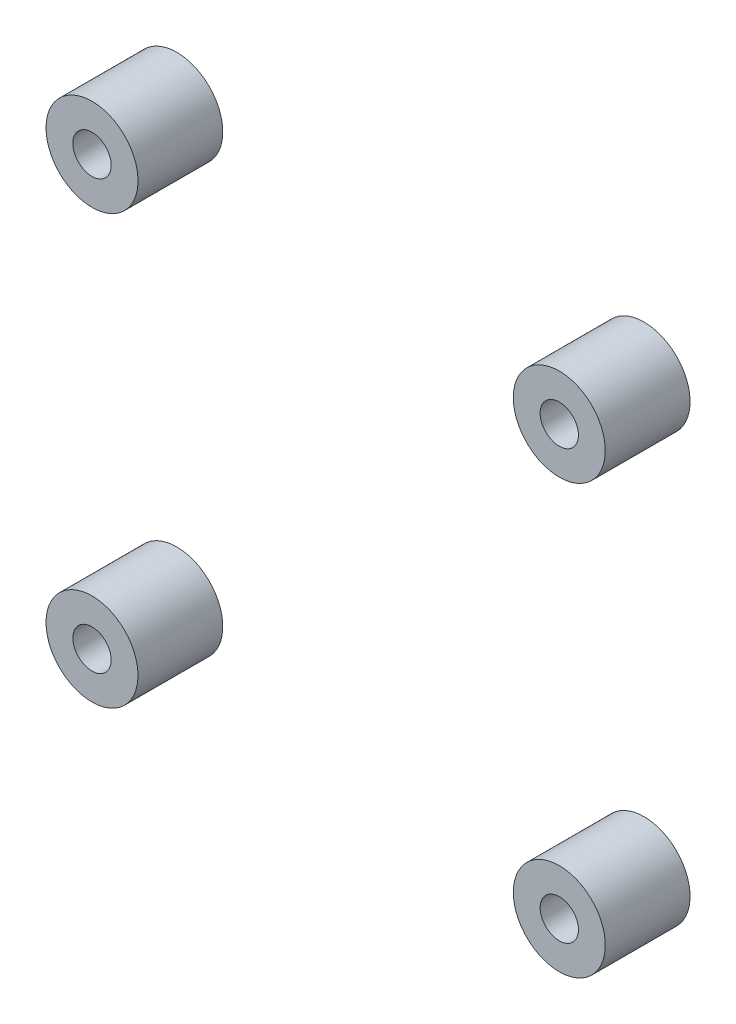
SolidWorks part; units mm, degrees
ref_plane "Front Plane" through (0, 0, 0) normal (0, 0, 1) x (1, 0, 0)
ref_plane "Top Plane" through (0, 0, 0) normal (0, 1, 0) x (1, 0, 0)
ref_plane "Right Plane" through (0, 0, 0) normal (1, 0, 0) x (0, 0, -1)
sketch "Sketch2" plane through (0, 0, -8.179) normal (0, 0, 1) x (1, 0, 0)
  circle A0 centre (20.6285, -11.8987) radius 1.25
  circle A1 centre (20.6285, -11.8987) radius 1 construction
  circle A2 centre (20.6285, -11.8987) radius 3
  circle A3 centre (-9.8515, -11.8987) radius 1.25
  circle A4 centre (-9.8515, -11.8987) radius 3
  circle A5 centre (-9.8515, 16.0413) radius 1.25
  circle A6 centre (-9.8515, 16.0413) radius 3
  circle A7 centre (20.6285, 16.0413) radius 1.25
  circle A8 centre (20.6285, 16.0413) radius 3
  circle A9 centre (-9.8515, -11.8987) radius 1 construction
  circle A10 centre (20.6285, -11.8987) radius 1.25 construction
  point P2 (0, 0)
  point P6 (0, 0)
  point P18 (0, 0)
  point P19 (0, 0)
  point P20 (0, 0)
  point P21 (0, 0)
  point P22 (15.24, 13.999)
  dimension "D3" = 1.75
  dimension "D1" = 2
  dimension "D2" = 2
extrude "Boss-Extrude2" add sketch "Sketch2" along normal offset from surface (5.53 mm away) 0.3
